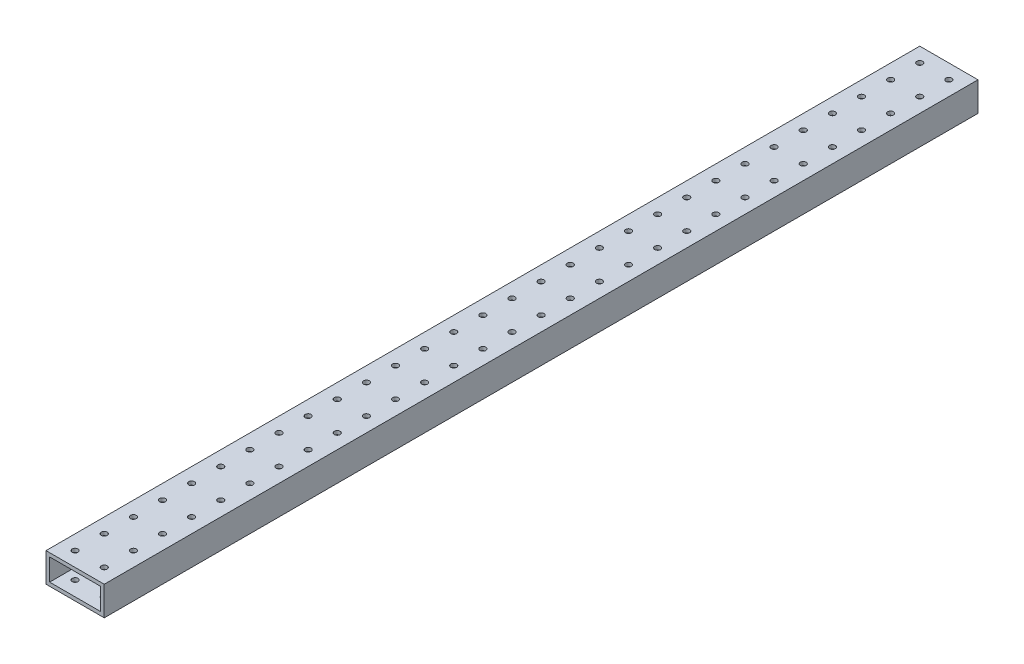
SolidWorks part; units mm, degrees
ref_plane "Front Plane" through (0, 0, 0) normal (0, 0, 1) x (1, 0, 0)
ref_plane "Top Plane" through (0, 0, 0) normal (0, 1, 0) x (1, 0, 0)
ref_plane "Right Plane" through (0, 0, 0) normal (1, 0, 0) x (0, 0, -1)
sketch "Sketch1" plane through (0, 0, 0) normal (0, 0, 1) x (1, 0, 0)
  line L0 (19.05, -9.525) -> (25.4, -12.7) construction
  line L1 (-25.4, -12.7) -> (25.4, -12.7)
  line L2 (-25.4, -12.7) -> (-25.4, 12.7)
  line L3 (-25.4, 12.7) -> (25.4, 12.7)
  line L4 (25.4, -12.7) -> (25.4, 12.7)
  line L5 (-25.4, -12.7) -> (-19.05, -9.525) construction
  line L6 (-25.4, 12.7) -> (-19.05, 9.525) construction
  line L7 (-22.225, -9.525) -> (22.225, -9.525)
  line L8 (-22.225, -9.525) -> (-22.225, 9.525)
  line L9 (-22.225, 9.525) -> (22.225, 9.525)
  line L10 (22.225, -9.525) -> (22.225, 9.525)
  line L13 (19.05, 9.525) -> (25.4, 12.7) construction
  point P0 (0, 0)
  point P6 (0, 0)
  dimension "D1" = 50.8
  dimension "D2" = 25.4
  dimension "D3" = 44.45
  dimension "D4" = 19.05
extrude "Boss-Extrude1" add sketch "Sketch1" along normal blind 762
sketch "Sketch2" plane through (0, 12.7, 0) normal (0, 1, 0) x (1, 0, 0)
  line L0 (-25.4, -381) -> (25.4, -381) construction
  line L1 (-25.4, -762) -> (-25.4, 0) construction
  line L2 (25.4, -762) -> (25.4, 0) construction
  line L3 (25.4, 0) -> (-25.4, 0) construction
  circle A0 centre (-12.7, -12.7) radius 2.54
  circle A1 centre (12.7, -12.7) radius 2.54
  circle A4 centre (-12.7, -38.1) radius 2.54
  circle A5 centre (12.7, -38.1) radius 2.54
  circle A6 centre (-12.7, -63.5) radius 2.54
  circle A7 centre (12.7, -63.5) radius 2.54
  circle A8 centre (-12.7, -88.9) radius 2.54
  circle A9 centre (12.7, -88.9) radius 2.54
  circle A10 centre (-12.7, -114.3) radius 2.54
  circle A11 centre (12.7, -114.3) radius 2.54
  circle A12 centre (-12.7, -139.7) radius 2.54
  circle A13 centre (12.7, -139.7) radius 2.54
  circle A14 centre (-12.7, -165.1) radius 2.54
  circle A15 centre (12.7, -165.1) radius 2.54
  circle A16 centre (-12.7, -190.5) radius 2.54
  circle A17 centre (12.7, -190.5) radius 2.54
  circle A18 centre (-12.7, -215.9) radius 2.54
  circle A19 centre (12.7, -215.9) radius 2.54
  circle A20 centre (-12.7, -241.3) radius 2.54
  circle A21 centre (12.7, -241.3) radius 2.54
  circle A22 centre (-12.7, -266.7) radius 2.54
  circle A23 centre (12.7, -266.7) radius 2.54
  circle A24 centre (-12.7, -292.1) radius 2.54
  circle A25 centre (12.7, -292.1) radius 2.54
  circle A26 centre (-12.7, -317.5) radius 2.54
  circle A27 centre (12.7, -317.5) radius 2.54
  circle A28 centre (-12.7, -342.9) radius 2.54
  circle A29 centre (12.7, -342.9) radius 2.54
  circle A30 centre (-12.7, -368.3) radius 2.54
  circle A31 centre (12.7, -368.3) radius 2.54
  circle A32 centre (12.7, -393.7) radius 2.54
  circle A33 centre (-12.7, -393.7) radius 2.54
  circle A34 centre (12.7, -419.1) radius 2.54
  circle A35 centre (-12.7, -419.1) radius 2.54
  circle A36 centre (12.7, -444.5) radius 2.54
  circle A37 centre (-12.7, -444.5) radius 2.54
  circle A38 centre (12.7, -469.9) radius 2.54
  circle A39 centre (-12.7, -469.9) radius 2.54
  circle A40 centre (12.7, -495.3) radius 2.54
  circle A41 centre (-12.7, -495.3) radius 2.54
  circle A42 centre (12.7, -520.7) radius 2.54
  circle A43 centre (-12.7, -520.7) radius 2.54
  circle A44 centre (12.7, -546.1) radius 2.54
  circle A45 centre (-12.7, -546.1) radius 2.54
  circle A46 centre (12.7, -571.5) radius 2.54
  circle A47 centre (-12.7, -571.5) radius 2.54
  circle A48 centre (12.7, -596.9) radius 2.54
  circle A49 centre (-12.7, -596.9) radius 2.54
  circle A50 centre (12.7, -622.3) radius 2.54
  circle A51 centre (-12.7, -622.3) radius 2.54
  circle A52 centre (12.7, -647.7) radius 2.54
  circle A53 centre (-12.7, -647.7) radius 2.54
  circle A54 centre (12.7, -673.1) radius 2.54
  circle A55 centre (-12.7, -673.1) radius 2.54
  circle A56 centre (12.7, -698.5) radius 2.54
  circle A57 centre (-12.7, -698.5) radius 2.54
  circle A58 centre (12.7, -723.9) radius 2.54
  circle A59 centre (-12.7, -723.9) radius 2.54
  circle A60 centre (12.7, -749.3) radius 2.54
  circle A61 centre (-12.7, -749.3) radius 2.54
  dimension "D1" = 12.7
  dimension "D3" = 12.7
  dimension "D2" = 12.7
  dimension "D4" = 15
extrude "Cut-Extrude1" cut sketch "Sketch2" against normal up to surface (25.4 mm away) up to face at (0, -12.7, 381)
